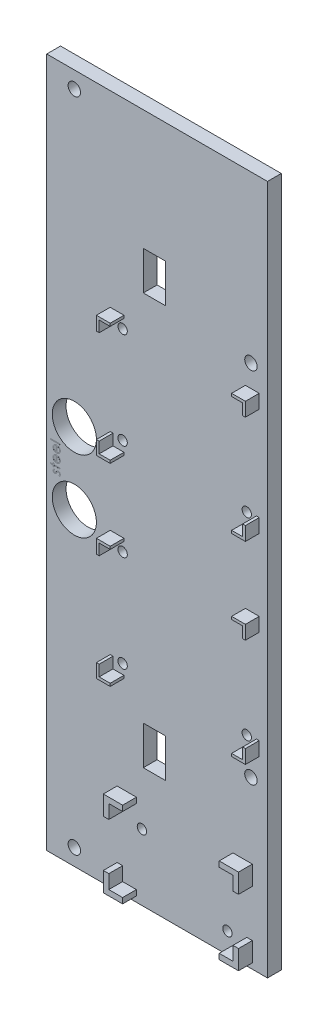
SolidWorks part; units mm, degrees
material "PLA"
ref_plane "정면" through (0, 0, 0) normal (0, 0, 1) x (1, 0, 0)
ref_plane "윗면" through (0, 0, 0) normal (0, 1, 0) x (1, 0, 0)
ref_plane "우측면" through (0, 0, 0) normal (1, 0, 0) x (0, 0, -1)
sketch "스케치1" plane through (0, 0, 0) normal (0, 0, 1) x (1, 0, 0)
  line L1 (-40, 125) -> (40, 125)
  line L2 (-40, 125) -> (-40, -125)
  line L3 (-40, -125) -> (40, -125)
  line L4 (40, 125) -> (40, -125)
  line L5 (-40, 125) -> (40, -125) construction
  line L6 (-40, -125) -> (40, 125) construction
  point P0 (0, 0)
  dimension "D1" = 80
  dimension "D2" = 250
extrude "보스-돌출1" add sketch "스케치1" along normal blind 5
sketch "스케치2" plane through (0, 0, 5) normal (0, 0, -1) x (-1, 0, 0)
  line L0 (35.1023, 125) -> (35.1023, -125) construction
  line L1 (-40, 125) -> (40, 125) construction
  line L2 (40, -125) -> (-40, -125) construction
  text T0 "steel\r\n"
extrude "temp" cut sketch "스케치2" along normal blind 0.01
sketch "스케치3" plane through (0, 0, 5) normal (0, 0, 1) x (1, 0, 0)
  line L0 (-12, -13) -> (-17, -13)
  line L1 (-17, -13) -> (-17, -18)
  line L2 (-17, -18) -> (-16, -18)
  line L3 (-16, -18) -> (-16, -14)
  line L4 (-16, -14) -> (-12, -14)
  line L5 (-12, -14) -> (-12, -13)
  line L6 (7.5, -35) -> (12.5, -35) construction
  line L7 (10, -32.5) -> (10, -37.5) construction
  line L8 (-40, -125) -> (40, -125) construction
  line L9 (40, -125) -> (40, 125) construction
  line L10 (32, -14) -> (32, -13)
  line L11 (36, -14) -> (32, -14)
  line L12 (36, -18) -> (36, -14)
  line L13 (37, -18) -> (36, -18)
  line L14 (37, -13) -> (37, -18)
  line L15 (32, -13) -> (37, -13)
  line L16 (32, -57) -> (37, -57)
  line L17 (37, -57) -> (37, -52)
  line L18 (37, -52) -> (36, -52)
  line L19 (36, -52) -> (36, -56)
  line L20 (36, -56) -> (32, -56)
  line L21 (32, -56) -> (32, -57)
  line L22 (-12, -56) -> (-12, -57)
  line L23 (-16, -56) -> (-12, -56)
  line L24 (-16, -52) -> (-16, -56)
  line L25 (-17, -52) -> (-16, -52)
  line L26 (-17, -57) -> (-17, -52)
  line L27 (-12, -57) -> (-17, -57)
  line L28 (-12, 0) -> (12, 0) construction
  line L29 (10, 32.5) -> (10, 37.5) construction
  line L30 (7.5, 35) -> (12.5, 35) construction
  line L31 (-12, 57) -> (-17, 57)
  line L32 (-17, 57) -> (-17, 52)
  line L33 (-17, 52) -> (-16, 52)
  line L34 (-16, 52) -> (-16, 56)
  line L35 (-16, 56) -> (-12, 56)
  line L36 (-12, 56) -> (-12, 57)
  line L37 (32, 56) -> (32, 57)
  line L38 (36, 56) -> (32, 56)
  line L39 (36, 52) -> (36, 56)
  line L40 (37, 52) -> (36, 52)
  line L41 (37, 57) -> (37, 52)
  line L42 (32, 57) -> (37, 57)
  line L43 (32, 13) -> (37, 13)
  line L44 (37, 13) -> (37, 18)
  line L45 (37, 18) -> (36, 18)
  line L46 (36, 18) -> (36, 14)
  line L47 (36, 14) -> (32, 14)
  line L48 (32, 14) -> (32, 13)
  line L49 (-12, 14) -> (-12, 13)
  line L50 (-16, 14) -> (-12, 14)
  line L51 (-16, 18) -> (-16, 14)
  line L52 (-17, 18) -> (-16, 18)
  line L53 (-17, 13) -> (-17, 18)
  line L54 (-12, 13) -> (-17, 13)
  point P2 (10, -35)
  point P64 (10, 35)
  dimension "D1" = 5
  dimension "D2" = 1
  dimension "D3" = 1
  dimension "D4" = 5
  dimension "D5" = 26
  dimension "D6" = 21
  dimension "D7" = 5
  dimension "D8" = 5
  dimension "D9" = 90
  dimension "D10" = 30
extrude "보스-돌출2" add sketch "스케치3" along normal blind 5
sketch "스케치4" plane through (0, 0, 5) normal (0, 0, 1) x (1, 0, 0)
  line L0 (-40, 125) -> (-40, -125) construction
  line L1 (-5, -67.5) -> (3, -67.5)
  line L2 (-5, -67.5) -> (-5, -81.5)
  line L3 (-5, -81.5) -> (3, -81.5)
  line L4 (3, -67.5) -> (3, -81.5)
  line L5 (-5, 81.5) -> (3, 81.5)
  line L6 (-5, 81.5) -> (-5, 67.5)
  line L7 (-5, 67.5) -> (3, 67.5)
  line L8 (3, 81.5) -> (3, 67.5)
  line L9 (-40, -125) -> (40, -125) construction
  line L10 (40, 125) -> (-40, 125) construction
  dimension "D1" = 14
  dimension "D2" = 14
  dimension "D3" = 8
  dimension "D4" = 8
  dimension "D5" = 35
  dimension "D6" = 35
  dimension "D7" = 43.5
  dimension "D8" = 43.5
extrude "컷-돌출1" cut sketch "스케치4" against normal blind 10
hole_wizard "M3 여유 구멍1" positions "스케치6" profile "스케치7" hole size "M3" standard "KS" end condition through all
sketch "스케치6" plane through (0, 0, 5) normal (0, 0, 1) x (1, 0, 0)
  line L0 (-16, 56) -> (-12, 56) construction
  line L1 (-16, 52) -> (-16, 56) construction
  line L2 (32, 56) -> (36, 56) construction
  line L3 (36, 56) -> (36, 52) construction
  line L4 (36, 18) -> (36, 14) construction
  line L5 (36, 14) -> (32, 14) construction
  line L6 (-12, 14) -> (-16, 14) construction
  line L7 (-16, 14) -> (-16, 18) construction
  line L8 (-16, -14) -> (-12, -14) construction
  line L9 (-16, -18) -> (-16, -14) construction
  line L10 (36, -14) -> (36, -18) construction
  line L11 (32, -14) -> (36, -14) construction
  line L12 (36, -56) -> (32, -56) construction
  line L13 (36, -52) -> (36, -56) construction
  line L14 (-12, -56) -> (-16, -56) construction
  line L15 (-16, -56) -> (-16, -52) construction
  point P0 (-12.5, 17.5)
  point P2 (32.5, 17.5)
  point P4 (32.5, 52.5)
  point P6 (-12.5, 52.5)
  point P8 (32.5, -17.5)
  point P10 (-12.5, -17.5)
  point P12 (-12.5, -52.5)
  point P14 (32.5, -52.5)
  dimension "D1" = 3.5
  dimension "D2" = 3.5
  dimension "D3" = 3.5
  dimension "D4" = 3.5
  dimension "D5" = 3.5
  dimension "D6" = 3.5
  dimension "D7" = 3.5
  dimension "D8" = 3.5
  dimension "D9" = 3.5
  dimension "D10" = 3.5
  dimension "D11" = 3.5
  dimension "D12" = 3.5
  dimension "D13" = 3.5
  dimension "D14" = 3.5
  dimension "D15" = 3.5
  dimension "D16" = 3.5
sketch "스케치7" plane through (-12.5, 17.5, 5) normal (1, 0, 0) x (0, -1, 0)
  line L0 (0, 0) -> (0, 5)
  line L1 (0, 5) -> (1.7, 5)
  line L2 (1.7, 5) -> (1.7, 0)
  line L5 (1.7, 0) -> (0, 0)
  line L11 (0, -6.35) -> (0, 107.95) construction
  dimension "관통 구멍 지름" = 3.4
  dimension "관통 구멍 깊이" = 5
sketch "스케치9" plane through (0, 0, 5) normal (0, 0, 1) x (1, 0, 0)
  line L0 (-14.5, -92) -> (-14.5, -99)
  line L1 (-14.5, -99) -> (-12.5, -99)
  line L2 (-12.5, -99) -> (-12.5, -94)
  line L3 (-12.5, -94) -> (-7.5, -94)
  line L4 (-7.5, -94) -> (-7.5, -92)
  line L5 (-7.5, -92) -> (-14.5, -92)
  line L6 (10, -113.5559) -> (10, -101.4441) construction
  line L7 (-7.8146, -107.5) -> (27.8146, -107.5) construction
  line L8 (40, -125) -> (40, 125) construction
  line L9 (3, -67.5) -> (-5, -67.5) construction
  line L10 (27.5, -92) -> (34.5, -92)
  line L11 (27.5, -94) -> (27.5, -92)
  line L12 (32.5, -94) -> (27.5, -94)
  line L13 (32.5, -99) -> (32.5, -94)
  line L14 (34.5, -99) -> (32.5, -99)
  line L15 (34.5, -92) -> (34.5, -99)
  line L16 (-14.5, -92) -> (-14.5, -99)
  line L17 (-14.5, -99) -> (-12.5, -99)
  line L18 (-12.5, -99) -> (-12.5, -94)
  line L19 (-12.5, -94) -> (-7.5, -94)
  line L20 (-7.5, -94) -> (-7.5, -92)
  line L21 (-7.5, -92) -> (-14.5, -92)
  line L22 (27.5, -92) -> (34.5, -92)
  line L23 (27.5, -94) -> (27.5, -92)
  line L24 (32.5, -94) -> (27.5, -94)
  line L25 (32.5, -99) -> (32.5, -94)
  line L26 (34.5, -99) -> (32.5, -99)
  line L27 (34.5, -92) -> (34.5, -99)
  line L28 (34.5, -123) -> (34.5, -116)
  line L29 (32.5, -116) -> (32.5, -121)
  line L30 (34.5, -123) -> (34.5, -116)
  line L31 (32.5, -116) -> (32.5, -121)
  line L32 (34.5, -116) -> (32.5, -116)
  line L33 (32.5, -121) -> (27.5, -121)
  line L34 (27.5, -121) -> (27.5, -123)
  line L35 (27.5, -123) -> (34.5, -123)
  line L36 (-7.5, -123) -> (-14.5, -123)
  line L37 (-7.5, -121) -> (-7.5, -123)
  line L38 (-12.5, -121) -> (-7.5, -121)
  line L39 (-12.5, -116) -> (-12.5, -121)
  line L40 (-14.5, -116) -> (-12.5, -116)
  line L41 (-14.5, -123) -> (-14.5, -116)
  line L42 (34.5, -116) -> (32.5, -116)
  line L43 (32.5, -121) -> (27.5, -121)
  line L44 (27.5, -121) -> (27.5, -123)
  line L45 (27.5, -123) -> (34.5, -123)
  line L46 (-7.5, -123) -> (-14.5, -123)
  line L47 (-7.5, -121) -> (-7.5, -123)
  line L48 (-12.5, -121) -> (-7.5, -121)
  line L49 (-12.5, -116) -> (-12.5, -121)
  line L50 (-14.5, -116) -> (-12.5, -116)
  line L51 (-14.5, -123) -> (-14.5, -116)
  point P10 (10, -107.5)
  dimension "D1" = 13.5
  dimension "D2" = 2
  dimension "D3" = 2
  dimension "D4" = 5
  dimension "D5" = 5
  dimension "D6" = 22.5
  dimension "D7" = 30
  dimension "D8" = 40
extrude "보스-돌출3" add sketch "스케치9" along normal blind 5 contours L41 L36 L37 L38 L39 L40 | L34 L35 L28 L32 L29 L33 | L15 L10 L11 L12 L13 L14 | L4 L5 L0 L1 L2 L3
hole_wizard "M3 여유 구멍2" positions "스케치13" profile "스케치12" hole size "M3" standard "KS" end condition through all
sketch "스케치13" plane through (0, 0, 5) normal (0, 0, 1) x (1, 0, 0)
  line L3 (-12.5, -121) -> (-7.5, -121) construction
  line L4 (-12.5, -99) -> (-12.5, -94) construction
  line L6 (-12.5, -94) -> (-7.5, -94) construction
  line L7 (32.5, -116) -> (32.5, -121) construction
  point P0 (-5.5, -101)
  point P7 (25.5, -117.5)
  dimension "D1" = 7
  dimension "D2" = 7
  dimension "D3" = 7
  dimension "D4" = 3.5
sketch "스케치12" plane through (-5.5, -101, 5) normal (1, 0, 0) x (0, -1, 0)
  line L0 (0, 0) -> (0, 5)
  line L1 (0, 5) -> (1.7, 5)
  line L2 (1.7, 5) -> (1.7, 0)
  line L5 (1.7, 0) -> (0, 0)
  line L11 (0, -6.35) -> (0, 107.95) construction
  dimension "관통 구멍 지름" = 3.4
  dimension "관통 구멍 깊이" = 5
hole_wizard "M4 여유 구멍1" positions "스케치14" profile "스케치15" hole size "M4" standard "KS" end condition through all
sketch "스케치14" plane through (0, 0, 5) normal (0, 0, 1) x (1, 0, 0)
  line L0 (40, 125) -> (-40, 125) construction
  line L1 (-40, 125) -> (-40, -125) construction
  line L2 (40, -125) -> (40, 125) construction
  line L5 (-40, -125) -> (40, -125) construction
  point P0 (-30, -119)
  point P2 (34, -65)
  point P4 (34, 65)
  point P6 (-30, 119)
  dimension "D1" = 6
  dimension "D2" = 10
  dimension "D3" = 6
  dimension "D4" = 60
  dimension "D5" = 60
  dimension "D6" = 6
  dimension "D7" = 10
  dimension "D8" = 6
sketch "스케치15" plane through (-30, -119, 5) normal (1, 0, 0) x (0, -1, 0)
  line L0 (0, 0) -> (0, 5)
  line L1 (0, 5) -> (2.25, 5)
  line L2 (2.25, 5) -> (2.25, 0)
  line L5 (2.25, 0) -> (0, 0)
  line L11 (0, -6.35) -> (0, 107.95) construction
  dimension "관통 구멍 지름" = 4.5
  dimension "관통 구멍 깊이" = 5
sketch "스케치16" plane through (0, 0, 5) normal (0, 0, 1) x (1, 0, 0)
  line L0 (-40, 125) -> (-40, -125) construction
  circle A0 centre (-30, -13) radius 8
  circle A1 centre (-30, 13) radius 8
  point P6 (-40, 0)
  dimension "D1" = 16
  dimension "D2" = 16
  dimension "D3" = 10
  dimension "D4" = 10
  dimension "D5" = 26
  dimension "D6" = 13
extrude "컷-돌출2" cut sketch "스케치16" against normal blind 10
